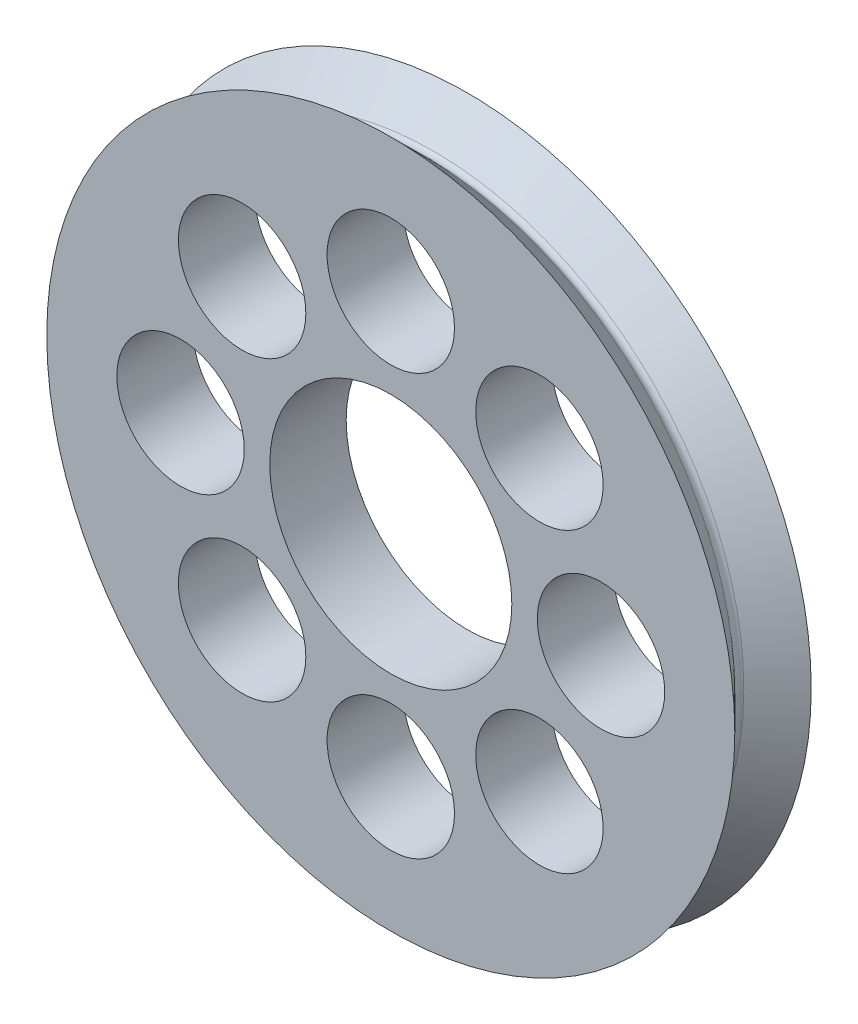
SolidWorks part; units mm, degrees
ref_plane "前视基准面" through (0, 0, 0) normal (0, 0, 1) x (1, 0, 0)
ref_plane "上视基准面" through (0, 0, 0) normal (0, 1, 0) x (1, 0, 0)
ref_plane "右视基准面" through (0, 0, 0) normal (1, 0, 0) x (0, 0, -1)
sketch "草图2" plane through (0, 0, 0) normal (0, 1, 0) x (1, 0, 0)
  line L0 (-52.219, 0) -> (144.5041, 0) construction
  line L1 (9.5, 3) -> (9.5, -3)
  line L2 (9.5, -3) -> (27, -3)
  line L3 (27, -3) -> (24.3536, -0.3536)
  line L4 (24.3536, 0.3536) -> (27, 3)
  line L5 (27, 3) -> (9.5, 3)
  line L6 (0, 0) -> (0, 26.9573) construction
  arc A0 (24.3536, 0.3536) -> (24.3536, -0.3536) centre (24.7071, 0) ccw
  point P10 (24, 0)
  dimension "D5" = 0.5
  dimension "D1" = 9.5
  dimension "D2" = 6
  dimension "D3" = 27
  dimension "D4" = 24
revolve "旋转1" add sketch "草图2" angle 360 about L6
sketch "草图6" plane through (0, 0, 3) normal (0, 0, 1) x (1, 0, 0)
  line L0 (0, 0) -> (16.5, 0) construction
  circle A0 centre (0, 0) radius 16.5 construction
  circle A1 centre (16.5, 0) radius 5
  circle A2 centre (11.6673, -11.6673) radius 5
  circle A3 centre (0, -16.5) radius 5
  circle A4 centre (-11.6673, -11.6673) radius 5
  circle A5 centre (-16.5, 0) radius 5
  circle A6 centre (-11.6673, 11.6673) radius 5
  circle A7 centre (0, 16.5) radius 5
  circle A8 centre (11.6673, 11.6673) radius 5
  point P22 (0, 0)
  dimension "D1" = 33
  dimension "D2" = 10
  dimension "D3" = 8
extrude "切除-拉伸2" cut sketch "草图6" against normal blind 10
